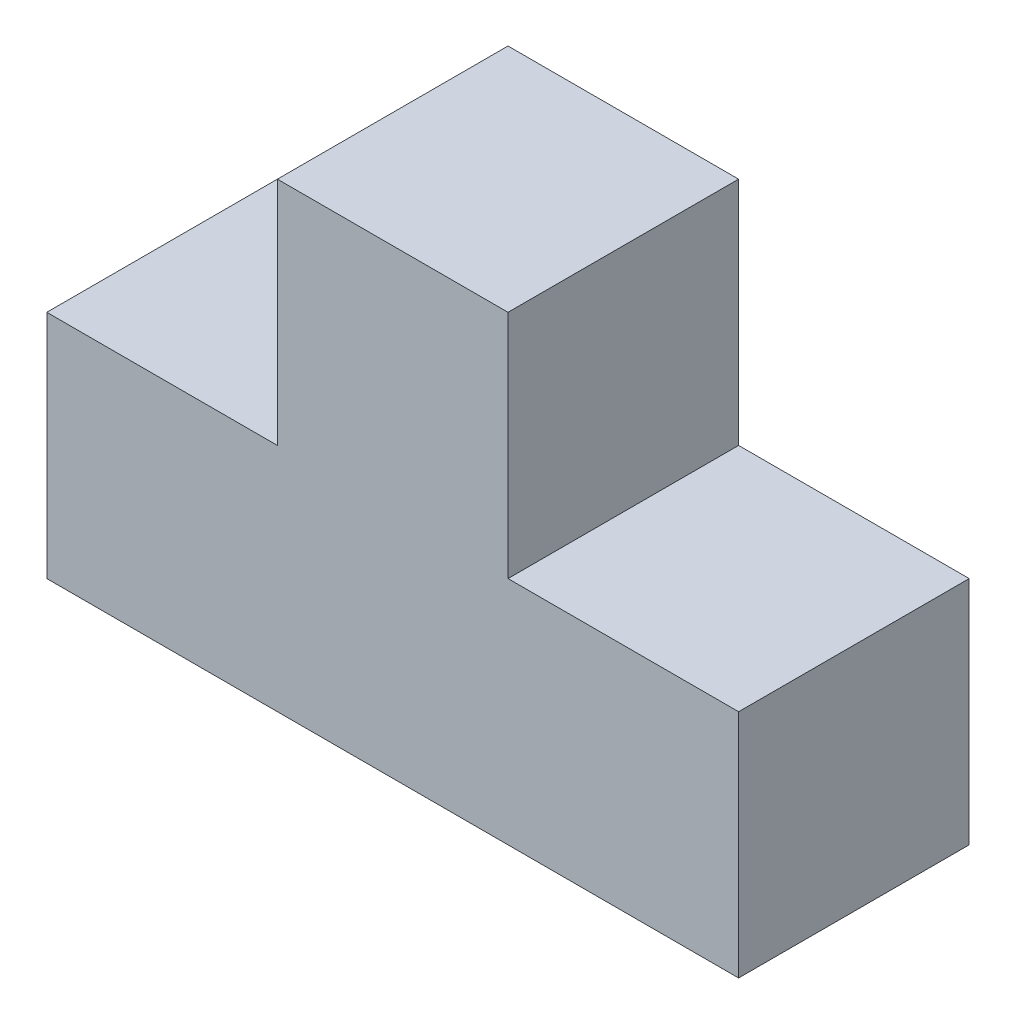
SolidWorks part; units mm, degrees
ref_plane "Plan de face" through (0, 0, 0) normal (0, 0, 1) x (1, 0, 0)
ref_plane "Plan de dessus" through (0, 0, 0) normal (0, 1, 0) x (1, 0, 0)
ref_plane "Plan de droite" through (0, 0, 0) normal (1, 0, 0) x (0, 0, -1)
sketch "Esquisse1" plane through (0, 0, 0) normal (0, 0, 1) x (1, 0, 0)
  line L0 (0, 0) -> (900, 0)
  line L1 (900, 0) -> (900, 300)
  line L2 (900, 300) -> (600, 300)
  line L3 (600, 300) -> (600, 600)
  line L4 (600, 600) -> (300, 600)
  line L5 (300, 600) -> (300, 300)
  line L6 (300, 300) -> (0, 300)
  line L7 (0, 300) -> (0, 0)
  dimension "D1" = 900
  dimension "D2" = 300
  dimension "D3" = 300
  dimension "D4" = 600
  dimension "D5" = 300
  dimension "D6" = 300
extrude "Boss.-Extru.1" add sketch "Esquisse1" along normal blind 300
